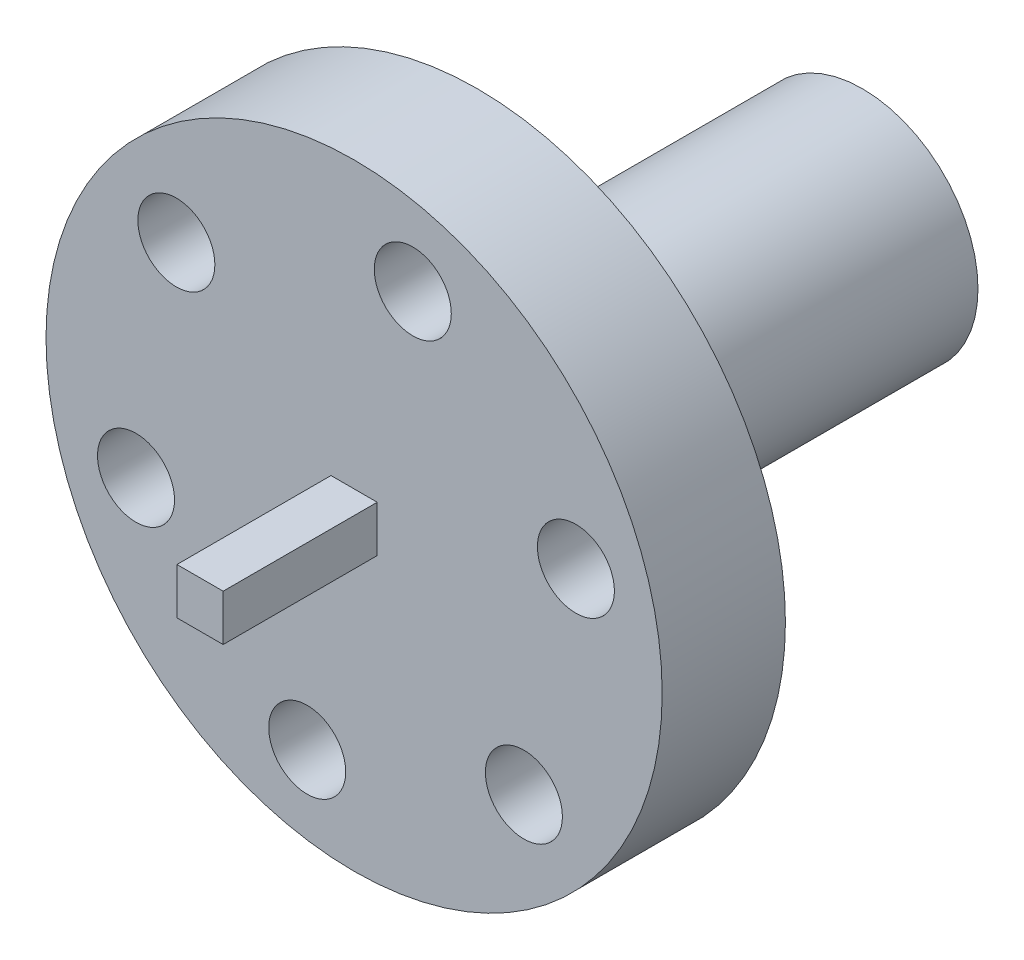
SolidWorks part; units mm, degrees
ref_plane "Front Plane" through (0, 0, 0) normal (0, 0, 1) x (1, 0, 0)
ref_plane "Top Plane" through (0, 0, 0) normal (0, 1, 0) x (1, 0, 0)
ref_plane "Right Plane" through (0, 0, 0) normal (1, 0, 0) x (0, 0, -1)
sketch "Sketch1" plane through (0, 0, 0) normal (0, 0, 1) x (1, 0, 0)
  line L0 (3.8092, 14.5083) -> (0, 0) construction
  circle A0 centre (0, 0) radius 20
  circle A1 centre (0, 0) radius 15 construction
  circle A2 centre (3.8092, 14.5083) radius 2.5
  circle A3 centre (14.3979, 4.2075) radius 2.5
  circle A4 centre (11.022, -10.174) radius 2.5
  circle A5 centre (-3.0441, -14.6874) radius 2.5
  circle A6 centre (-14.1574, -4.9549) radius 2.5
  circle A7 centre (-11.5388, 9.5836) radius 2.5
  point P15 (0.0003, 0.0002)
  dimension "D1" = 40
  dimension "D2" = 30
  dimension "D3" = 5
extrude "Boss-Extrude1" add sketch "Sketch1" along normal blind 8
sketch "Sketch2" plane through (0, 0, 8) normal (0, 0, 1) x (1, 0, 0)
  line L1 (1.5, 1.5) -> (-1.5, 1.5)
  line L2 (1.5, 1.5) -> (1.5, -1.5)
  line L3 (1.5, -1.5) -> (-1.5, -1.5)
  line L4 (-1.5, 1.5) -> (-1.5, -1.5)
  line L5 (1.5, 1.5) -> (-1.5, -1.5) construction
  line L6 (1.5, -1.5) -> (-1.5, 1.5) construction
  point P0 (0, 0)
  dimension "D1" = 3
  dimension "D2" = 3
extrude "Boss-Extrude2" add sketch "Sketch2" along normal blind 10
sketch "Sketch3" plane through (0, 0, 0) normal (0, 0, -1) x (-1, 0, 0)
  circle A0 centre (0, 0) radius 7.5
  dimension "D1" = 15
extrude "Boss-Extrude3" add sketch "Sketch3" along normal blind 25
sketch "Sketch4" plane through (0, 0, 0) normal (0, 0, -1) x (-1, 0, 0)
  circle A0 centre (0, 0) radius 10
  dimension "D1" = 20
extrude "Boss-Extrude4" add sketch "Sketch4" along normal blind 5
